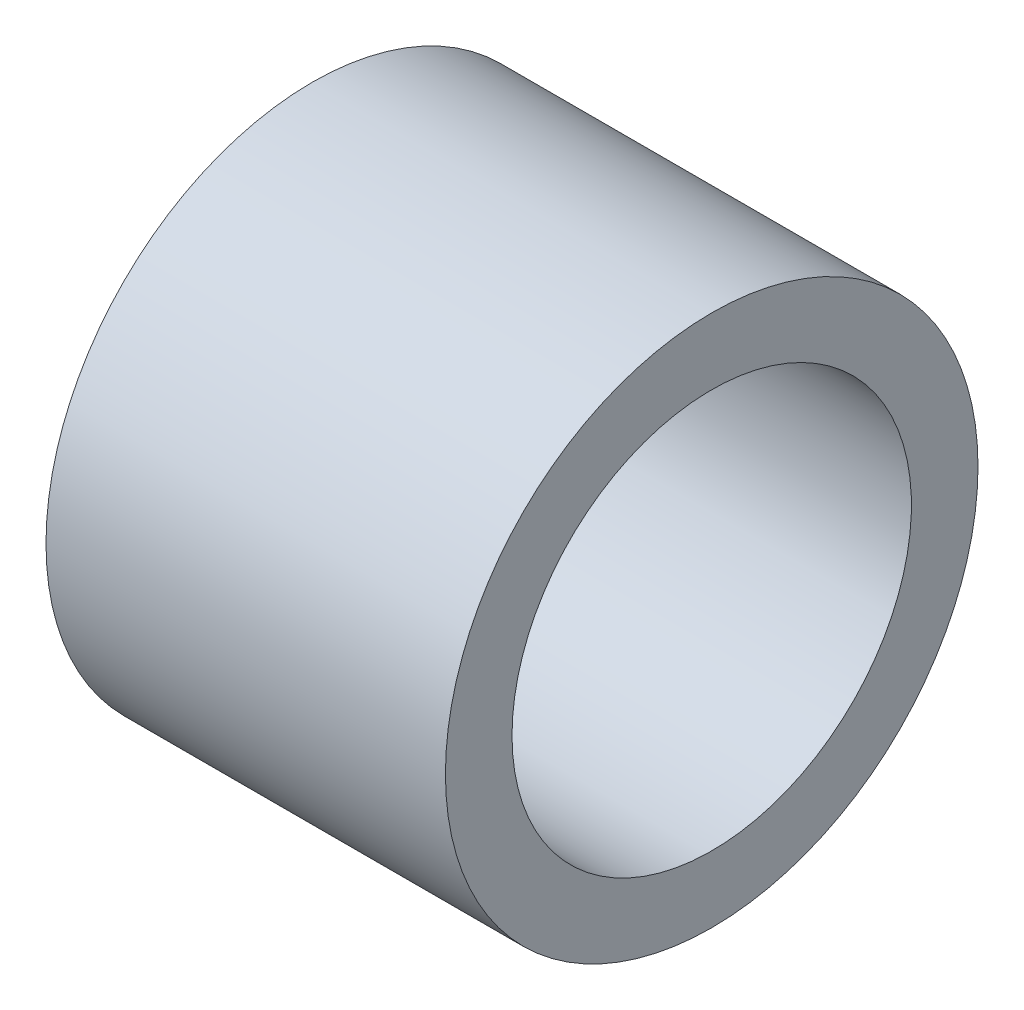
SolidWorks part; units mm, degrees
ref_plane "Front Plane" through (0, 0, 0) normal (0, 0, 1) x (1, 0, 0)
ref_plane "Top Plane" through (0, 0, 0) normal (0, 1, 0) x (1, 0, 0)
ref_plane "Right Plane" through (0, 0, 0) normal (1, 0, 0) x (0, 0, -1)
sketch "Sketch1" plane through (0, 0, 0) normal (1, 0, 0) x (0, 0, -1)
  circle A0 centre (0, 0) radius 12.7
  circle A1 centre (0, 0) radius 9.525
  dimension "D1" = 25.4
  dimension "D2" = 19.05
extrude "Boss-Extrude1" add sketch "Sketch1" along normal mid plane 19.05
